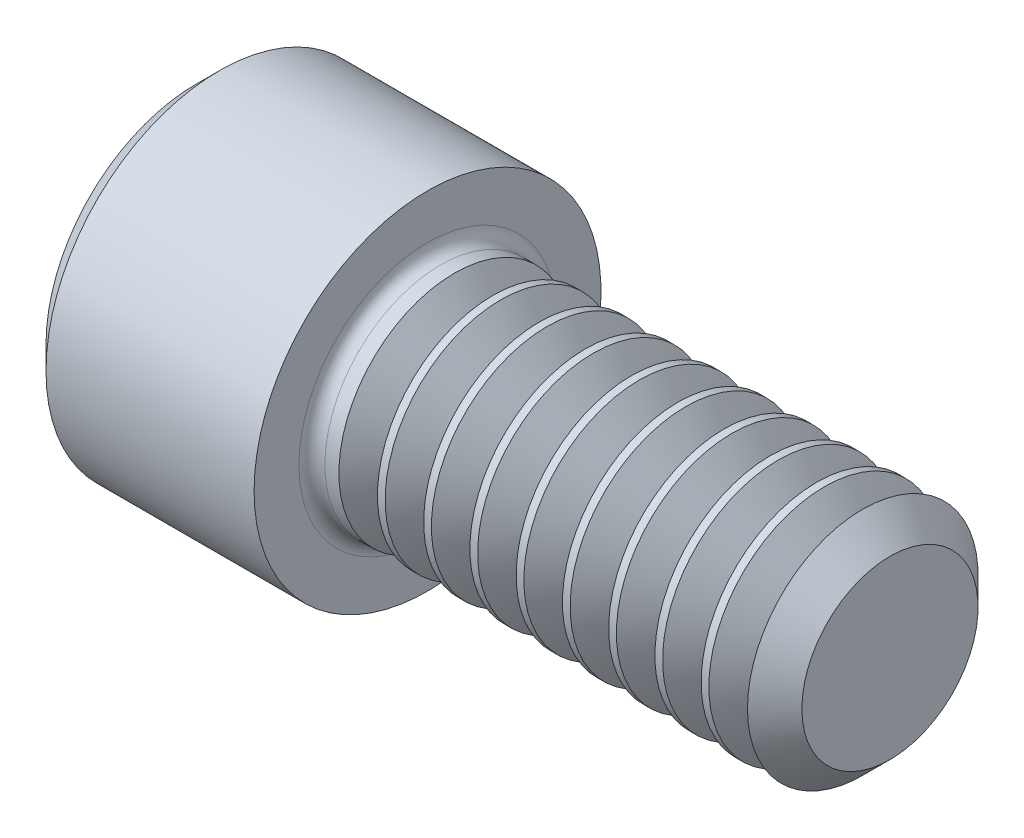
SolidWorks part; units mm, degrees
revolve "Base-Revolve" add sketch "BodySke"
sketch "BodySke" plane through (0, 0, 0) normal (0, 0, 1) x (1, 0, 0)
  line L0 (0, 0) -> (0, 4.1275)
  line L1 (0.635, 4.7625) -> (6.35, 4.7625)
  line L2 (6.35, 4.7625) -> (6.35, 3.175)
  line L3 (6.35, 3.175) -> (18.2943, 3.175)
  line L4 (19.05, 2.4193) -> (19.05, 0)
  line L5 (19.05, 0) -> (0, 0)
  line L6 (-31.75, 0) -> (127, 0) construction
  line L7 (0, 4.1275) -> (0.635, 4.7625)
  line L8 (19.05, 2.4193) -> (18.2943, 3.175)
  line L9 (0, -4.1275) -> (0.635, -4.7625) construction
  line L10 (19.05, -2.4193) -> (18.2943, -3.175) construction
  line L11 (7.62, 9.525) -> (7.62, 3.175) construction
  line L12 (6.35, 9.525) -> (6.35, 3.175) construction
  line L13 (-19.05, 9.525) -> (-19.05, 3.175) construction
  dimension "Diameter" = 6.35
  dimension "Head_ht" = 6.35
  dimension "Length" = 12.7
  dimension "Body_ch_ang" = 45
  dimension "Head_dia" = 9.525
  dimension "Head_ch_ang" = 45
  dimension "Head_side_ht" = 5.715
  dimension "Minor_dia" = 4.8387
  dimension "Advance" = 1.27
  dimension "Thread_nom" = 12.7
  dimension "Thread_length" = 38.1
cosmetic thread "ThreadCosmetic" [suppressed]
fillet "Fillet1" radius 0.3556 1 edges at (6.35, 0, 3.175)
ref_plane "Plane1" through (0, 0, 0) normal (0, 0, 1) x (1, 0, 0)
ref_plane "Plane2" through (0, 0, 0) normal (0, 1, 0) x (1, 0, 0)
ref_plane "Plane3" through (0, 0, 0) normal (1, 0, 0) x (0, 0, -1)
sketch "Sketch2" plane through (0, 0, 0) normal (0, 0, 1) x (1, 0, 0)
  line L0 (0, 2.3813) -> (3.048, 2.3813)
  line L1 (3.048, 2.3813) -> (4.4228, 0)
  line L2 (-31.75, 0) -> (127, 0) construction
  line L3 (4.4228, 0) -> (0, 0)
  line L4 (0, 0) -> (0, 2.3813)
  line L5 (0, 4.1275) -> (0, -4.1275) construction
  line L6 (0, 0) -> (47.625, 0) construction
  line L7 (6.35, -4.7625) -> (6.35, 4.7625) construction
  dimension "D1" = 2.3813
  dimension "D2" = 60
revolve "Hex-PreBroach" cut sketch "Sketch2" angle 360 about L6
sketch "Sketch3" plane through (0, 0, 0) normal (-1, 0, 0) x (0, 0.5, 0.866)
  line L0 (1.3748, 2.3813) -> (-1.3748, 2.3813)
  line L1 (-1.3748, 2.3813) -> (-2.7496, 0)
  line L2 (1.3748, 2.3813) -> (2.7496, 0)
  line L3 (1.3748, -2.3812) -> (2.7496, 0)
  line L4 (1.3748, -2.3812) -> (-1.3748, -2.3812)
  line L5 (-1.3748, -2.3812) -> (-2.7496, 0)
  dimension "D1" = 2.3813
  dimension "D2" = 2.3813
  dimension "Hex_size" = 4.7625
extrude "Hex" cut sketch "Sketch3" against normal blind 3.048
sketch "Sketch4" plane through (0, 0, 0) normal (-1, 0, 0) x (0, 0, 1)
  line L0 (0, 0) -> (2.8067, 0)
  line L1 (0, 0) -> (6.1484, 3.5498) construction
  line L2 (0, 0) -> (1.4033, 2.4307)
  line L3 (2.3336, 0.614) -> (2.6851, 0.817)
  line L4 (1.6986, 1.7139) -> (2.0501, 1.9169)
  arc A0 (2.3336, 0.614) -> (1.6986, 1.7139) centre (0, 0) ccw
  arc A1 (2.8067, 0) -> (2.6851, 0.817) centre (0, 0) ccw
  arc A2 (1.4033, 2.4307) -> (2.0501, 1.9169) centre (0, 0) cw
  dimension "D1" = 30
  dimension "D2" = 60
  dimension "Spline_p_dim" = 1.27
  dimension "D3" = 0.635
extrude "Spline" [suppressed] cut sketch "Sketch4" against normal blind 3.048
pattern_circular "CirPattern1" [suppressed] count 6 every 60
sketch "Sketch5" plane through (0, 0, 0) normal (0, 0, 1) x (1, 0, 0)
  line L0 (-31.75, 0) -> (127, 0) construction
  line L2 (0, 4.1275) -> (0, -4.1275) construction
  circle A0 centre (2.159, 0) radius 0.5905
  dimension "Drilled_hole_dia" = 1.1811
  dimension "Drilled_hole_loc" = 2.159
extrude "Hole" [suppressed] cut sketch "Sketch5" against normal through all and the other way through all
pattern_circular "Drilled-4" [suppressed] count 2 every 60
pattern_circular "Drilled-6" [suppressed] count 3 every 60
sketch "ThdSchSke" plane through (0, 0, 0) normal (0, 0, 1) x (1, 0, 0)
  line L0 (7.62, -2.4193) -> (7.0909, -3.175)
  line L1 (7.62, -2.4193) -> (8.1491, -3.175)
  line L2 (8.1491, -3.175) -> (8.1491, -3.9688)
  line L3 (-3.175, 0) -> (5.1513, 0) construction
  line L5 (8.1491, -3.9688) -> (7.0909, -3.9688)
  line L6 (7.0909, -3.9688) -> (7.0909, -3.175)
  line L7 (0, 4.1275) -> (0, -4.1275) construction
  dimension "Thread_minor" = 4.8387
  dimension "Diameter" = 6.35
  dimension "Start" = 7.62
revolve "ThreadSchematic" cut sketch "ThdSchSke" angle 360 about L3
pattern_linear "ThdSchPat" count 9 spacing 1.27 along (1, 0, 0) of "ThreadSchematic"
equation "\"D2@Sketch3\" = \"Hex_size@Sketch3\" / 2"
equation "\"D1@Sketch3\" = \"Hex_size@Sketch3\" / 2"
equation "\"D1@Sketch2\" = \"Hex_size@Sketch3\" / 2"
equation "\"D3@Sketch4\" = \"Spline_p_dim@Sketch4\" / 2"
equation "\"Thread_minor@ThreadCosmetic\"  =  \"Minor_dia@BodySke\""
equation "\"D2@CirPattern1\" = 360 / \"Num_teeth@CirPattern1\""
equation "\"Wall_thickness@Sketch2\" = \"Head_ht@BodySke\" - \"Key_eng@Hex\""
equation "\"Thread_length@ThreadCosmetic\" = ((sgn( (\"Length@BodySke\" - \"Advance@BodySke\" ) - \"Thread_nom@BodySke\" )-1)*( (\"Length@BodySke\" - \"Advance@BodySke\" ) - \"Thread_nom@BodySke\" ))/-2+ \"Thread_nom@BodySke\""
equation "\"Thread_minor@ThdSchSke\" = \"Minor_dia@BodySke\""
equation "\"Diameter@ThdSchSke\" = \"Diameter@BodySke\""
equation "\"Overcut@ThdSchSke\" = \"Diameter@BodySke\" * 1.25"
equation "\"Start@ThdSchSke\" = \"Head_ht@BodySke\" + \"Length@BodySke\" - \"Thread_length@ThreadCosmetic\"  '---Non-countersunk---"
equation "\"Num_threads@ThdSchPat\" = int( \"Thread_length@ThreadCosmetic\" / \"Advance@BodySke\" + 0.999 )  + 1"
equation "\"Advance@ThdSchPat\" = \"Thread_length@ThreadCosmetic\" /  (\"Num_threads@ThdSchPat\" - 1) 'relax it"
equation "\"Num_threads@ThdSchPat\" = \"Num_threads@ThdSchPat\" - sgn( \"Num_threads@ThdSchPat\" - 1) '---chamfered tips only---"
